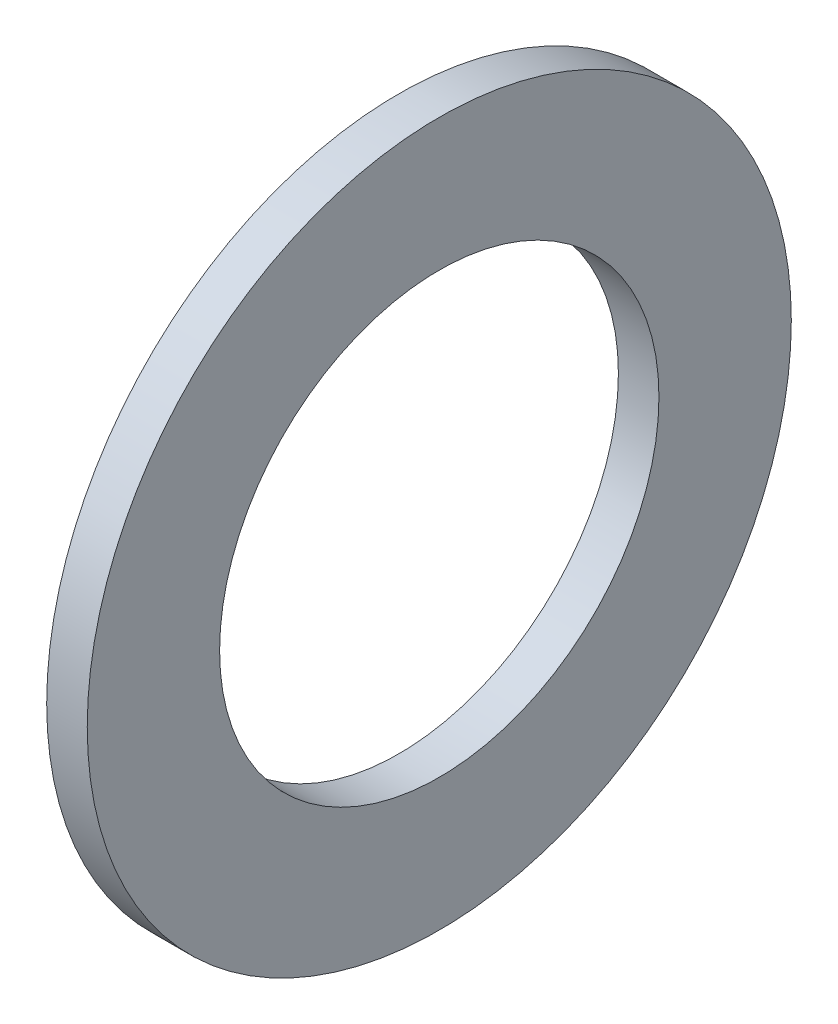
SolidWorks part; units mm, degrees
ref_plane "Front Plane" through (0, 0, 0) normal (0, 0, 1) x (1, 0, 0)
ref_plane "Top Plane" through (0, 0, 0) normal (0, 1, 0) x (1, 0, 0)
ref_plane "Right Plane" through (0, 0, 0) normal (1, 0, 0) x (0, 0, -1)
sketch "Sketch1" plane through (0, 0, 0) normal (1, 0, 0) x (0, 0, -1)
  circle A0 centre (0, 0) radius 4.953
  circle A1 centre (0, 0) radius 7.9375
  dimension "OD" = 9.906
  dimension "ID" = 15.875
extrude "Boss-Extrude1" add sketch "Sketch1" along normal blind 0.9144
